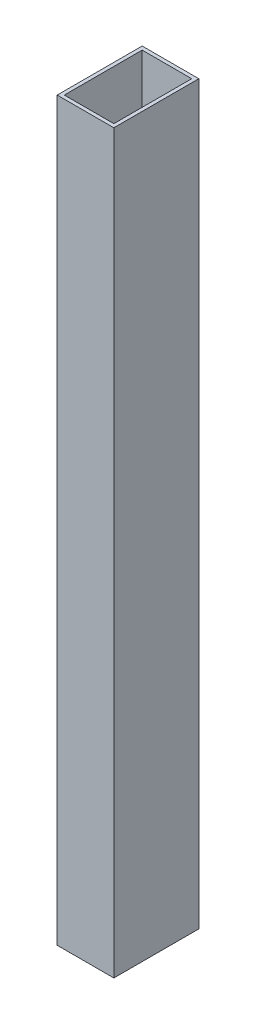
SolidWorks part; units mm, degrees
ref_plane "Front Plane" through (0, 0, 0) normal (0, 0, 1) x (1, 0, 0)
ref_plane "Top Plane" through (0, 0, 0) normal (0, 1, 0) x (1, 0, 0)
ref_plane "Right Plane" through (0, 0, 0) normal (1, 0, 0) x (0, 0, -1)
sketch "Sketch1" plane through (0, 0, 0) normal (0, 1, 0) x (1, 0, 0)
  line L1 (-25.4, 38.1) -> (25.4, 38.1)
  line L2 (-25.4, 38.1) -> (-25.4, -38.1)
  line L3 (-25.4, -38.1) -> (25.4, -38.1)
  line L4 (25.4, 38.1) -> (25.4, -38.1)
  line L5 (-25.4, 38.1) -> (25.4, -38.1) construction
  line L6 (-25.4, -38.1) -> (25.4, 38.1) construction
  point P0 (0, 0)
  dimension "D1" = 50.8
  dimension "D2" = 76.2
extrude "Boss-Extrude1" add sketch "Sketch1" along normal blind 660.4
shell "Shell1" thickness 3.175
